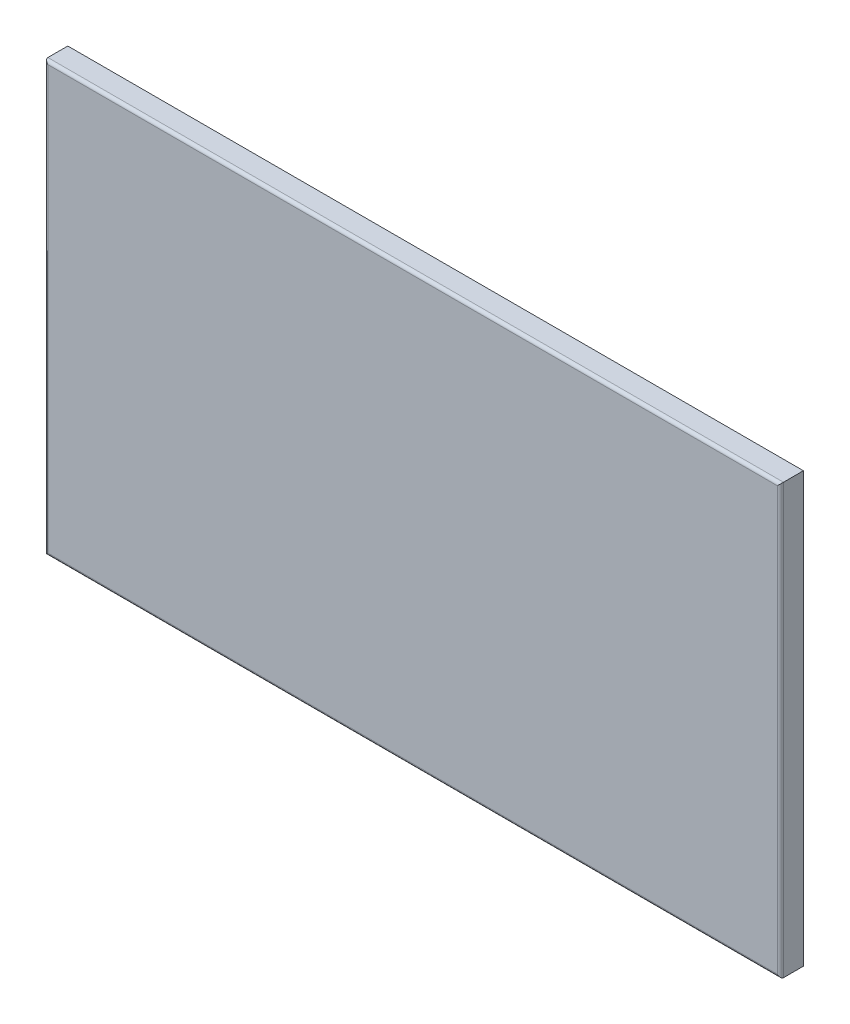
SolidWorks part; units mm, degrees
ref_plane "Front Plane" through (0, 0, 0) normal (0, 0, 1) x (1, 0, 0)
ref_plane "Top Plane" through (0, 0, 0) normal (0, 1, 0) x (1, 0, 0)
ref_plane "Right Plane" through (0, 0, 0) normal (1, 0, 0) x (0, 0, -1)
sketch "Sketch1" plane through (0, 0, 0) normal (0, 0, 1) x (1, 0, 0)
  line L1 (-304.8, -177.8) -> (304.8, -177.8)
  line L2 (-304.8, -177.8) -> (-304.8, 177.8)
  line L3 (-304.8, 177.8) -> (304.8, 177.8)
  line L4 (304.8, -177.8) -> (304.8, 177.8)
  line L5 (-304.8, -177.8) -> (304.8, 177.8) construction
  line L6 (-304.8, 177.8) -> (304.8, -177.8) construction
  point P0 (0, 0)
  dimension "D1" = 355.6
  dimension "D2" = 609.6
extrude "Boss-Extrude1" add sketch "Sketch1" along normal blind 2.54
sketch "Sketch2" plane through (0, 0, 2.54) normal (0, 0, 1) x (1, 0, 0)
  line L0 (302.26, 175.26) -> (-302.26, 175.26)
  line L1 (-302.26, 175.26) -> (-302.26, -175.26)
  line L2 (-302.26, -175.26) -> (302.26, -175.26)
  line L3 (302.26, -175.26) -> (302.26, 175.26)
  line L4 (304.8, -177.8) -> (304.8, 177.8)
  line L5 (304.8, 177.8) -> (-304.8, 177.8)
  line L6 (-304.8, 177.8) -> (-304.8, -177.8)
  line L7 (-304.8, -177.8) -> (304.8, -177.8)
  line L8 (304.8, -177.8) -> (304.8, 177.8)
  line L9 (304.8, 177.8) -> (-304.8, 177.8)
  line L10 (-304.8, 177.8) -> (-304.8, -177.8)
  line L11 (-304.8, -177.8) -> (304.8, -177.8)
  dimension "D1" = 0
  dimension "D2" = 2.54
extrude "Boss-Extrude2" add sketch "Sketch2" against normal blind 19.05
fillet "Fillet1" radius 2.54 4 edges at (0, -177.8, 2.54) (-304.8, 0, 2.54) (0, 177.8, 2.54) (304.8, 0, 2.54)
